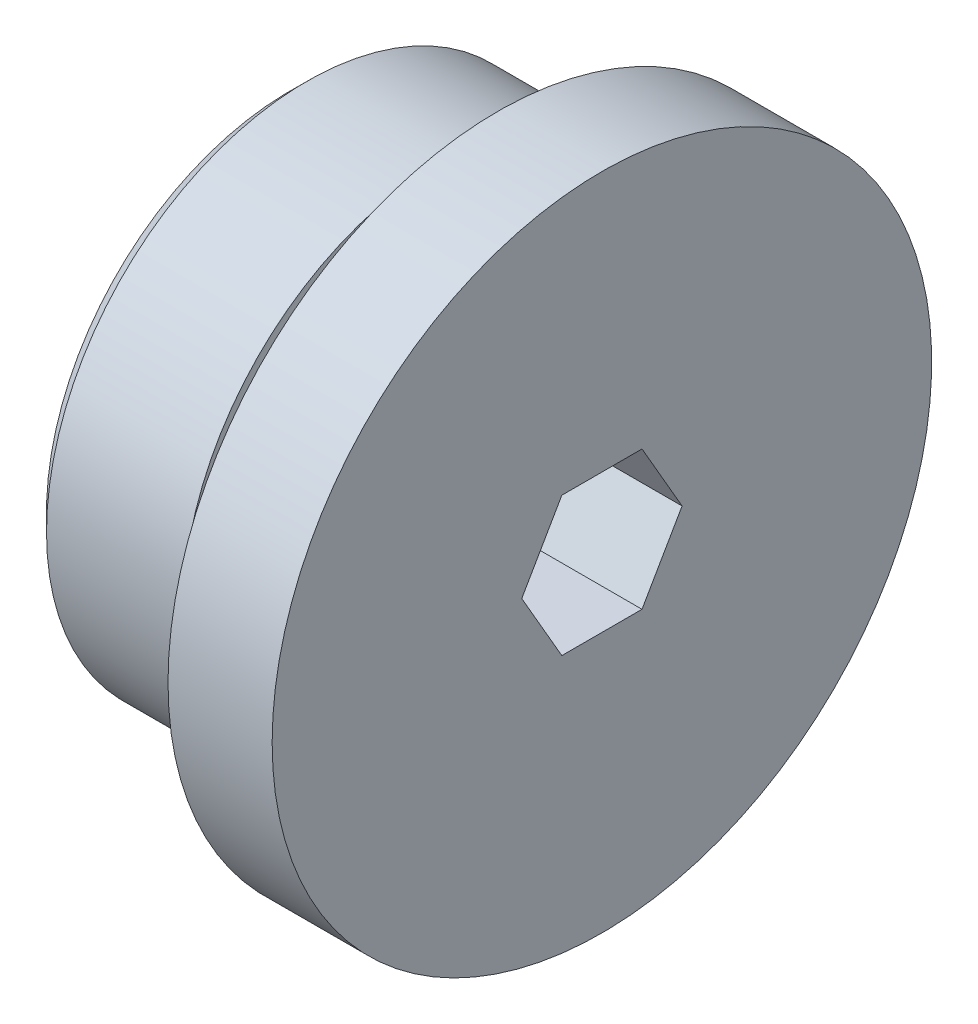
SolidWorks part; units mm, degrees
ref_plane "Plan de face" through (0, 0, 0) normal (0, 0, 1) x (1, 0, 0)
ref_plane "Plan de dessus" through (0, 0, 0) normal (0, 1, 0) x (1, 0, 0)
ref_plane "Plan de droite" through (0, 0, 0) normal (1, 0, 0) x (0, 0, -1)
sketch "Esquisse1" plane through (0, 0, 0) normal (0, 0, 1) x (1, 0, 0)
  line L0 (0, 0) -> (109.7255, 0) construction
  line L1 (0, 0) -> (0, 15)
  line L2 (0, 15) -> (8.8602, 15)
  line L3 (12, 15) -> (12, 19)
  line L4 (12, 19) -> (18, 19)
  line L5 (18, 19) -> (18, 0)
  line L6 (0, 0) -> (18, 0)
  arc A0 (8.8602, 15) -> (12, 15) centre (10.4301, 15) ccw
  dimension "D1" = 15
  dimension "D2" = 12
  dimension "D3" = 6
  dimension "D4" = 19
revolve "Révolution1" add sketch "Esquisse1" angle 360 about L0
cosmetic thread "Représentation de filetage1" parameters "D2"=28
sketch "Esquisse3" plane through (18, 0, 0) normal (1, 0, 0) x (0, 0, -1)
  line L0 (6.1678, 0) -> (-6.1678, 0) construction
  line L1 (-4.6188, 0) -> (-2.3094, 4)
  line L2 (0, 0) -> (-2.6829, 4.6469) construction
  line L3 (0, 0) -> (0, 6.5135) construction
  line L4 (0, 0) -> (2.6829, 4.6469) construction
  line L5 (4.6188, 0) -> (2.3094, 4)
  line L6 (-2.3094, 4) -> (2.3094, 4)
  line L7 (4.6188, 0) -> (2.3094, -4)
  line L8 (-2.3094, -4) -> (2.3094, -4)
  line L9 (-4.6188, 0) -> (-2.3094, -4)
  dimension "D1" = 60
  dimension "D2" = 4
hole_wizard "Diamètre du perçage Ø8.0 (8)1" positions "Esquisse3D2" profile "Esquisse5" hole size "Ø8.0" standard "Ansi Métrique"
sketch3d "Esquisse3D2"
  point P0 (0, 0, 0)
  point P4 (18, 0, 0)
sketch "Esquisse5" plane through (18, 0, 0) normal (0, 1, 0) x (0, 0, -1)
  line L0 (0, 0) -> (0, 12.4034)
  line L1 (0, 12.4034) -> (4, 10)
  line L2 (4, 10) -> (4, 0)
  line L5 (4, 0) -> (0, 0)
  line L10 (0, 12.4034) -> (-4, 10) construction
  line L11 (0, -6.35) -> (0, 107.95) construction
  dimension "Diamètre du perçage" = 8
  dimension "Profondeur du perçage" = 10
  dimension "Angle de pointe" = 118
extrude "Enlèv. mat.-Extru.1" cut sketch "Esquisse3" against normal blind 8
chamfer "Chanfrein1" distance 1 angle 45 1 edges at (0, 0, 15)
